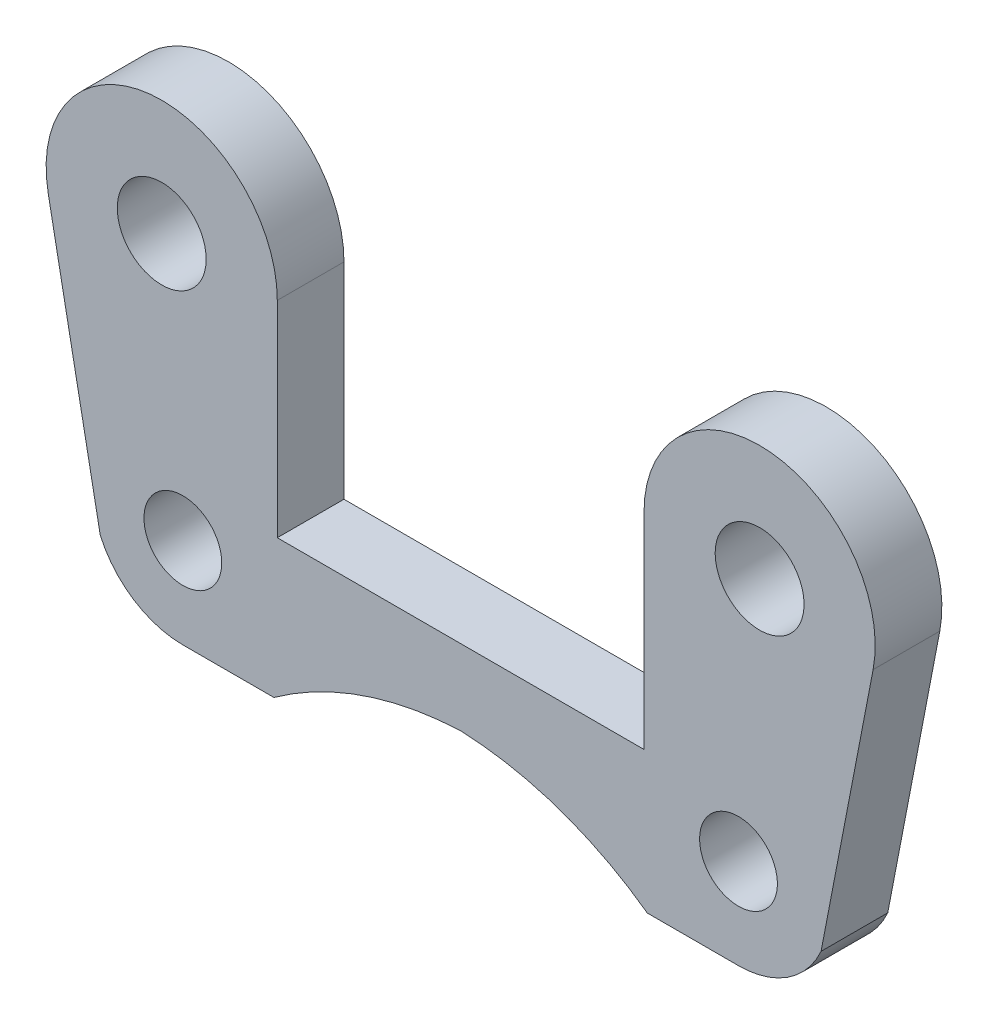
SolidWorks part; units mm, degrees
ref_plane "Front Plane" through (0, 0, 0) normal (0, 0, 1) x (1, 0, 0)
ref_plane "Top Plane" through (0, 0, 0) normal (0, 1, 0) x (1, 0, 0)
ref_plane "Right Plane" through (0, 0, 0) normal (1, 0, 0) x (0, 0, -1)
sketch "Sketch1" plane through (0, 0, 0) normal (0, 0, 1) x (1, 0, 0)
  line L0 (-39.5, 0) -> (39.5, 0) construction
  line L1 (0, 0) -> (0, -41.5) construction
  line L4 (-25, -41.5) -> (-16.8, -41.5)
  line L6 (-32.4314, -36.6683) -> (-37.1153, -12.3706)
  line L7 (-16.5, -28.9) -> (-16.5, -10.4017)
  line L8 (-16.5, -28.9) -> (16.5, -28.9)
  line L9 (-25, -41.5) -> (25, -41.5) construction
  line L10 (31.5, -41.5) -> (-31.5, -41.5) construction
  line L11 (-31.5, -41.5) -> (-39.5, 0) construction
  line L12 (31.5, -41.5) -> (39.5, 0) construction
  line L13 (16.5, -28.9) -> (16.5, -10.4017)
  line L14 (32.4314, -36.6683) -> (37.1153, -12.3706)
  line L15 (25, -41.5) -> (16.8, -41.5)
  arc A0 (0, -35.7) -> (-16.8, -41.5) centre (1.2023, -66.4136) ccw
  arc A1 (-25, -41.5) -> (-32.4314, -36.6683) centre (-25, -33.3692) cw
  arc A2 (-37.1153, -12.3706) -> (-16.5, -10.4017) centre (-26.9017, -10.4017) cw
  circle A3 centre (-26.9017, -10.4017) radius 4
  circle A4 centre (-25, -33.3692) radius 3.5
  circle A5 centre (25, -33.3692) radius 3.5
  circle A6 centre (26.9017, -10.4017) radius 4
  arc A7 (37.1153, -12.3706) -> (16.5, -10.4017) centre (26.9017, -10.4017) ccw
  arc A8 (25, -41.5) -> (32.4314, -36.6683) centre (25, -33.3692) ccw
  arc A9 (0, -35.7) -> (16.8, -41.5) centre (-1.2023, -66.4136) cw
  point P5 (0, 0)
  point P19 (0, -41.5)
  point P22 (0, 0)
  point P36 (0, -28.9)
  dimension "D9" = 8
  dimension "D10" = 7
  dimension "D1" = 5.8
  dimension "D2" = 79
  dimension "D3" = 50
  dimension "D4" = 41.5
  dimension "D5" = 8.2
  dimension "D6" = 16.5
  dimension "D7" = 31.5
  dimension "D8" = 12.6
extrude "Boss-Extrude1" add sketch "Sketch1" along normal blind 6
